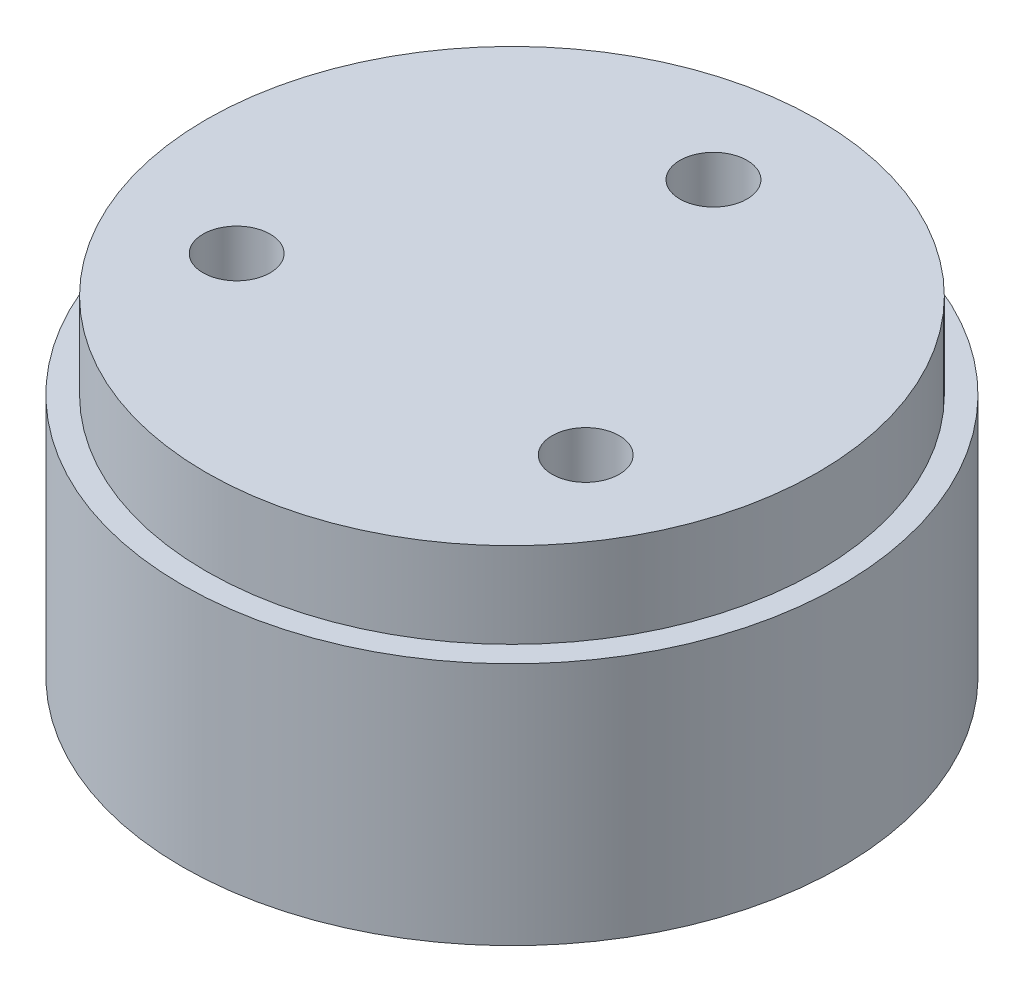
SolidWorks part; units mm, degrees
ref_plane "Front Plane" through (0, 0, 0) normal (0, 0, 1) x (1, 0, 0)
ref_plane "Top Plane" through (0, 0, 0) normal (0, 1, 0) x (1, 0, 0)
ref_plane "Right Plane" through (0, 0, 0) normal (1, 0, 0) x (0, 0, -1)
sketch "Sketch2" plane through (0, 0, 0) normal (0, 1, 0) x (1, 0, 0)
  circle A0 centre (0, 0) radius 27
  dimension "D1" = 54
extrude "Boss-Extrude2" add sketch "Sketch2" along normal blind 27
sketch "Sketch9" plane through (0, 0, 0) normal (0, -1, 0) x (-1, 0, 0)
  line L0 (-14.2981, -8.255) -> (0, 0) construction
  line L1 (0, 0) -> (0, 16.51) construction
  line L2 (0, 0) -> (14.2981, -8.255) construction
  point P0 (14.2981, -8.255)
  point P2 (0, 16.51)
  point P4 (-14.2981, -8.255)
  dimension "D1" = 120
  dimension "D2" = 120
  dimension "D3" = 16.51
hole_wizard "M5 Clearance Hole1" positions "Sketch9" profile "Sketch8" hole size "M5" standard "ANSI Metric" end condition up to next
sketch "Sketch8" plane through (-14.2981, 0, 8.255) normal (1, 0, 0) x (0, 0, -1)
  line L0 (0, 0) -> (0, 27)
  line L1 (0, 27) -> (2.75, 27)
  line L2 (2.75, 27) -> (2.75, 0)
  line L5 (2.75, 0) -> (0, 0)
  line L11 (0, -6.35) -> (0, 107.95) construction
  dimension "Thru Hole Dia." = 5.5
  dimension "Thru Hole Depth" = 27
sketch "Sketch10" plane through (0, 27, 0) normal (0, 1, 0) x (1, 0, 0)
  circle A0 centre (0, 0) radius 25.05
  circle A1 centre (0, 0) radius 27
  dimension "D1" = 50.1
extrude "Cut-Extrude1" cut sketch "Sketch10" against normal offset from surface (7 mm away) 20 up to face at (0, 0, -19.26)
